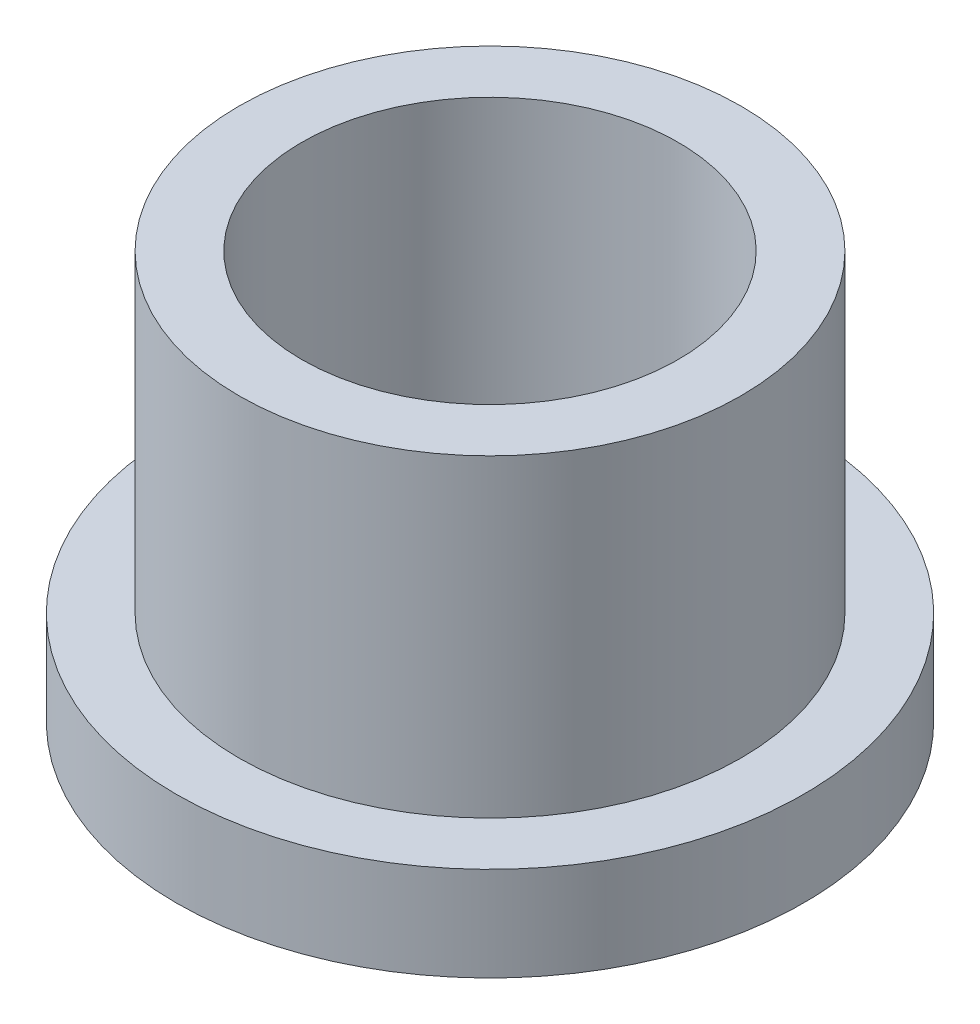
SolidWorks part; units mm, degrees
material "Copper"
ref_plane "Front Plane" through (0, 0, 0) normal (0, 0, 1) x (1, 0, 0)
ref_plane "Top Plane" through (0, 0, 0) normal (0, 1, 0) x (1, 0, 0)
ref_plane "Right Plane" through (0, 0, 0) normal (1, 0, 0) x (0, 0, -1)
sketch "Sketch2" plane through (0, 0, 0) normal (0, 1, 0) x (1, 0, 0)
  circle A0 centre (0, 0) radius 5
  dimension "D1" = 10
extrude "Boss-Extrude1" add sketch "Sketch2" along normal blind 1.5
sketch "Sketch3" plane through (0, 0, 0) normal (0, -1, 0) x (1, 0, 0)
  circle A0 centre (0, 0) radius 4
  dimension "D1" = 8
extrude "Boss-Extrude2" add sketch "Sketch3" against normal blind 6.5
sketch "Sketch4" plane through (0, 6.5, 0) normal (0, 1, 0) x (1, 0, 0)
  circle A0 centre (0, 0) radius 3
  dimension "D1" = 6
extrude "Cut-Extrude1" cut sketch "Sketch4" against normal through all
